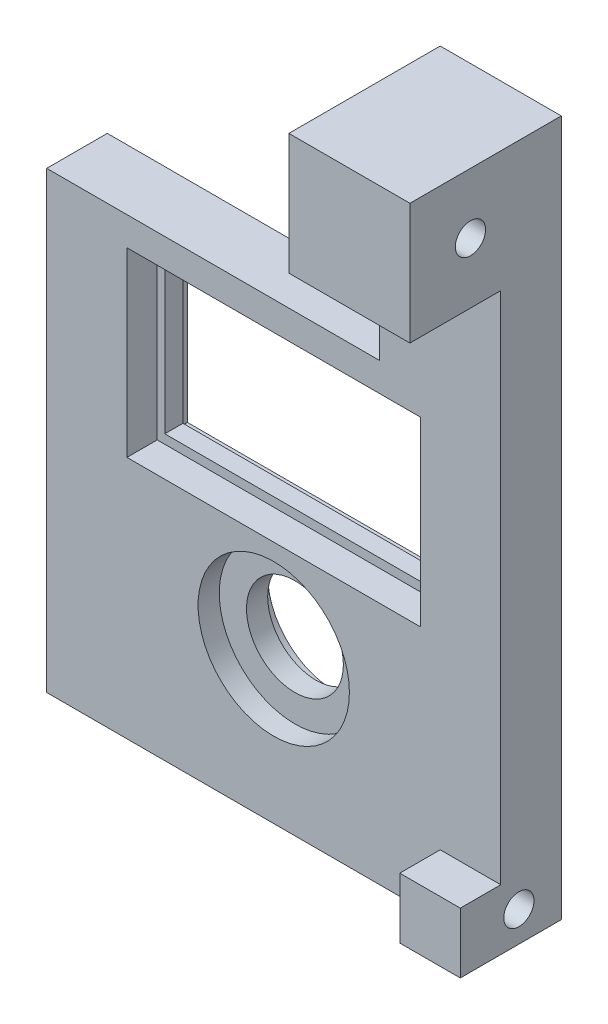
SolidWorks part; units mm, degrees
ref_plane "前视基准面" through (0, 0, 0) normal (0, 0, 1) x (1, 0, 0)
ref_plane "上视基准面" through (0, 0, 0) normal (0, 1, 0) x (1, 0, 0)
ref_plane "右视基准面" through (0, 0, 0) normal (1, 0, 0) x (0, 0, -1)
other "Configuration Table"
sketch "草图1" plane through (0, 0, 0) normal (0, 0, 1) x (1, 0, 0)
  line L1 (-37.5, -57.5) -> (37.5, -57.5)
  line L2 (-37.5, -57.5) -> (-37.5, 57.5)
  line L3 (-37.5, 57.5) -> (37.5, 57.5)
  line L4 (37.5, -57.5) -> (37.5, 57.5)
  line L5 (-37.5, -57.5) -> (37.5, 57.5) construction
  line L6 (-37.5, 57.5) -> (37.5, -57.5) construction
  point P0 (0, 0)
  dimension "D1" = 75
  dimension "D2" = 115
extrude "凸台-拉伸1" add sketch "草图1" along normal blind 10
sketch "草图2" plane through (0, 0, 10) normal (0, 0, 1) x (1, 0, 0)
  line L1 (-37.5, -57.5) -> (37.5, -57.5) construction
  circle A0 centre (0, -32.5) radius 8
  dimension "D2" = 16
  dimension "D1" = 25
extrude "切除-拉伸1" cut sketch "草图2" against normal up to next
sketch "草图3" plane through (0, 0, 10) normal (0, 0, 1) x (1, 0, 0)
  circle A0 centre (0, -32.5) radius 12.5
  dimension "D1" = 25
extrude "切除-拉伸2" cut sketch "草图3" against normal blind 3.5
sketch "草图4" plane through (0, 0, 0) normal (0, 0, -1) x (-1, 0, 0)
  circle A0 centre (0, -32.5) radius 11
  dimension "D1" = 22
extrude "切除-拉伸3" cut sketch "草图4" against normal blind 3
sketch "草图6" plane through (0, 0, 10) normal (0, 0, 1) x (1, 0, 0)
  line L0 (37.5, 57.5) -> (17.5, 57.5)
  line L1 (37.5, 57.5) -> (-37.5, 57.5) construction
  line L2 (17.5, 57.5) -> (17.5, 37.5)
  line L3 (17.5, 37.5) -> (37.5, 37.5)
  line L4 (37.5, -57.5) -> (37.5, 57.5) construction
  line L5 (37.5, 37.5) -> (37.5, 57.5)
  dimension "D1" = 20
  dimension "D2" = 20
extrude "凸台-拉伸2" add sketch "草图6" along normal blind 15
sketch "草图7" plane through (37.5, 0, 0) normal (1, 0, 0) x (0, 0, -1)
  line L0 (-10, -57.5) -> (-16.6818, -57.5)
  line L1 (-16.6818, -57.5) -> (-16.6818, -47.5)
  line L2 (-16.6818, -47.5) -> (-10, -47.5)
  line L3 (-10, -57.5) -> (-10, 37.5) construction
  line L4 (-10, -57.5) -> (-10, -47.5)
  dimension "D1" = 10
extrude "凸台-拉伸3" add sketch "草图7" against normal blind 10
sketch "草图8" plane through (0, 0, 0) normal (0, 0, -1) x (-1, 0, 0)
  line L0 (-17.5, 57.5) -> (-17.5, 17.5)
  line L1 (-37.5, 57.5) -> (37.5, 57.5) construction
  line L2 (-17.5, 17.5) -> (37.5, 17.5)
  line L3 (37.5, 57.5) -> (37.5, -57.5) construction
  line L4 (37.5, 17.5) -> (37.5, 57.5)
  line L5 (37.5, 57.5) -> (-17.5, 57.5)
  line L6 (-17.5, 57.5) -> (-17.5, 37.5) construction
  dimension "D1" = 40
extrude "切除-拉伸4" cut sketch "草图8" against normal up to next and the other way through all
sketch "草图9" plane through (0, 0, 0) normal (0, 0, -1) x (-1, 0, 0)
  line L0 (0, -57.5) -> (0, 49942.5) construction
  line L1 (-23, -15.7341) -> (23, -15.7341)
  line L2 (-23, -15.7341) -> (-23, 11.2659)
  line L3 (-23, 11.2659) -> (23, 11.2659)
  line L4 (23, -15.7341) -> (23, 11.2659)
  line L5 (-23, -15.7341) -> (23, 11.2659) construction
  line L6 (-23, 11.2659) -> (23, -15.7341) construction
  line L7 (37.5, -57.5) -> (-37.5, -57.5) construction
  point P0 (0, -2.2341)
  point P9 (0, -57.5)
  dimension "D1" = 46
  dimension "D2" = 27
extrude "切除-拉伸5" cut sketch "草图9" against normal up to next
sketch "草图10" plane through (0, 0, 0) normal (0, 0, -1) x (-1, 0, 0)
  line L0 (0, -57.5) -> (0, 49942.5) construction
  line L1 (-24.25, -17.2341) -> (24.25, -17.2341)
  line L2 (-24.25, -17.2341) -> (-24.25, 12.7659)
  line L3 (-24.25, 12.7659) -> (24.25, 12.7659)
  line L4 (24.25, -17.2341) -> (24.25, 12.7659)
  line L5 (-24.25, -17.2341) -> (24.25, 12.7659) construction
  line L6 (-24.25, 12.7659) -> (24.25, -17.2341) construction
  line L7 (37.5, -57.5) -> (-37.5, -57.5) construction
  line L8 (-23, -2.2341) -> (23, -2.2341) construction
  line L9 (-23, 11.2659) -> (-23, -15.7341) construction
  line L10 (23, -15.7341) -> (23, 11.2659) construction
  point P0 (0, -2.2341)
  point P10 (0, -57.5)
  dimension "D1" = 48.5
  dimension "D2" = 30
extrude "切除-拉伸6" cut sketch "草图10" against normal blind 2
sketch "草图11" plane through (0, 0, 10) normal (0, 0, 1) x (1, 0, 0)
  line L0 (0, -32.5) -> (0, 49967.5) construction
  line L1 (-23, -2.2341) -> (23, -2.2341) construction
  line L2 (-24.25, -17.2341) -> (24.25, -17.2341)
  line L3 (-24.25, -17.2341) -> (-24.25, 12.7659)
  line L4 (-24.25, 12.7659) -> (24.25, 12.7659)
  line L5 (24.25, -17.2341) -> (24.25, 12.7659)
  line L6 (-24.25, -17.2341) -> (24.25, 12.7659) construction
  line L7 (-24.25, 12.7659) -> (24.25, -17.2341) construction
  line L8 (-23, 11.2659) -> (-23, -15.7341) construction
  line L9 (23, -15.7341) -> (23, 11.2659) construction
  point P3 (0, -2.2341)
  point P14 (0, -2.2341)
  dimension "D1" = 48.5
  dimension "D2" = 30
extrude "切除-拉伸7" cut sketch "草图11" against normal offset from surface (5 mm away) 3 up to face at (0, -2.2341, 2)
sketch "草图12" plane through (37.5, 0, 0) normal (1, 0, 0) x (0, 0, -1)
  circle A0 centre (-15, 47.5) radius 2.5
  circle A1 centre (-7, -52.5) radius 2.5
  dimension "D1" = 5
  dimension "D2" = 5
extrude "切除-拉伸8" cut sketch "草图12" against normal blind 15
